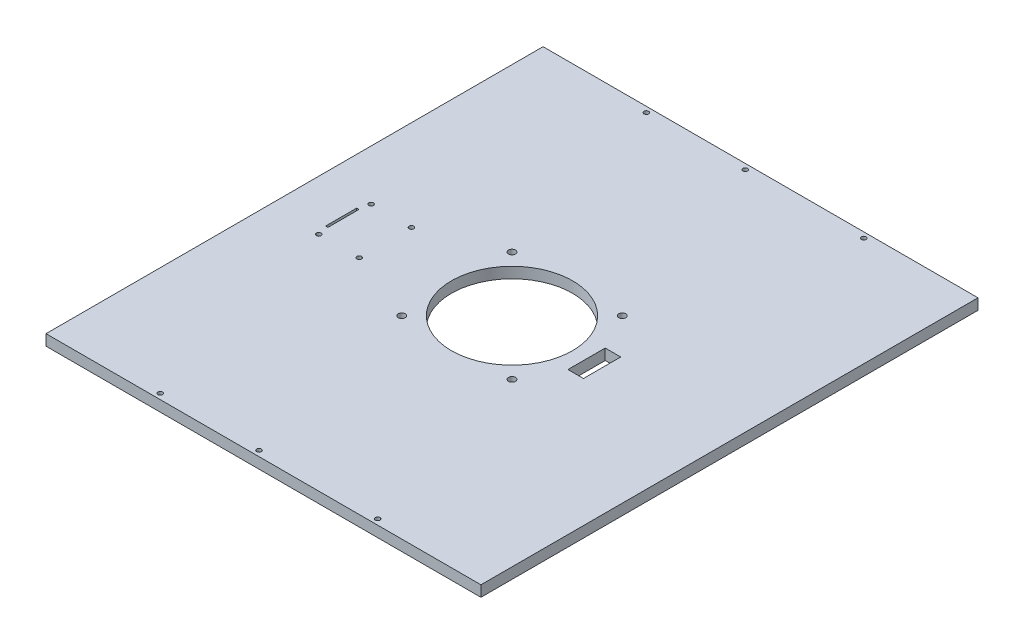
SolidWorks part; units mm, degrees
material "6061-T6 (SS)"
ref_plane "Front Plane" through (0, 0, 0) normal (0, 0, 1) x (1, 0, 0)
ref_plane "Top Plane" through (0, 0, 0) normal (0, 1, 0) x (1, 0, 0)
ref_plane "Right Plane" through (0, 0, 0) normal (1, 0, 0) x (0, 0, -1)
sketch "Sketch1" plane through (0, 0, 0) normal (0, 1, 0) x (1, 0, 0)
  line L0 (140, 0) -> (-140, 0) construction
  line L1 (-140, -160) -> (140, -160)
  line L2 (-140, -160) -> (-140, 160)
  line L3 (-140, 160) -> (140, 160)
  line L4 (140, -160) -> (140, 160)
  line L5 (-140, -160) -> (140, 160) construction
  line L6 (-140, 160) -> (140, -160) construction
  line L7 (-140, -160) -> (140, -160)
  line L8 (-140, 160) -> (140, 160)
  circle A0 centre (-70, 156.5) radius 1.5
  circle A1 centre (-6.3766, 156.5) radius 1.5
  circle A2 centre (70, 156.5) radius 1.5
  circle A3 centre (70, -156.5) radius 1.5
  circle A4 centre (-6.3766, -156.5) radius 1.5
  circle A5 centre (-70, -156.5) radius 1.5
  point P0 (0, 0)
  dimension "D3" = 3
  dimension "D4" = 3.5
  dimension "D7" = 3.5
  dimension "D8" = 3.5
  dimension "D1" = 280
  dimension "D2" = 320
  dimension "D5" = 70
  dimension "D6" = 70
extrude "Boss-Extrude1" add sketch "Sketch1" along normal blind 7 contours L1 L4 L3 L2 A4 A0 A1 A2 A3 A5
sketch "Sketch2" plane through (0, 7, 0) normal (0, 1, 0) x (1, 0, 0)
  line L0 (-110, 160) -> (-110, -160) construction
  line L1 (48, -12) -> (58, -12)
  line L2 (48, -12) -> (48, 12)
  line L3 (48, 12) -> (58, 12)
  line L4 (58, -12) -> (58, 12)
  line L5 (48, -12) -> (58, 12) construction
  line L6 (48, 12) -> (58, -12) construction
  line L7 (-140, 160) -> (140, 160) construction
  line L8 (-140, -160) -> (140, -160) construction
  line L9 (-140, -160) -> (-140, 160) construction
  line L10 (-110, 20) -> (-79.12, -20) construction
  line L11 (-110, 10) -> (-108.5, 10)
  line L12 (-110, 10) -> (-110, -10)
  line L13 (-110, -10) -> (-108.5, -10)
  line L14 (-108.5, 10) -> (-108.5, -10)
  line L15 (-110, -20) -> (-79.12, -20) construction
  line L16 (-110, -20) -> (-110, 20) construction
  line L17 (-110, 20) -> (-79.12, 20) construction
  line L18 (-79.12, -20) -> (-79.12, 20) construction
  line L19 (-79.12, 0) -> (-110, 0) construction
  line L20 (-94.56, 20) -> (-94.56, -20) construction
  circle A0 centre (0, 0) radius 39
  circle A1 centre (-35.5, 35.5) radius 2.25
  circle A2 centre (35.5, 35.5) radius 2.25
  circle A3 centre (35.5, -35.5) radius 2.25
  circle A4 centre (-35.5, -35.5) radius 2.25
  circle A5 centre (-107.5557, 16.8337) radius 1.5
  circle A6 centre (-81.5643, 16.8337) radius 1.5
  circle A7 centre (-107.5557, -16.8337) radius 1.5
  circle A8 centre (-81.5643, -16.8337) radius 1.5
  point P5 (53, 0)
  point P14 (0, 0)
  point P29 (-110, 0)
  point P34 (-79.12, 0)
  dimension "D1" = 78
  dimension "D2" = 4.5
  dimension "D3" = 35.5
  dimension "D4" = 35.5
  dimension "D14" = 3
  dimension "D15" = 4
  dimension "D6" = 10
  dimension "D7" = 24
  dimension "D8" = 53
  dimension "D9" = 30
  dimension "D10" = 1.5
  dimension "D11" = 20
  dimension "D12" = 40
  dimension "D13" = 30.88
  dimension "D5" = 4
extrude "Cut-Extrude1" cut sketch "Sketch2" against normal blind 10
